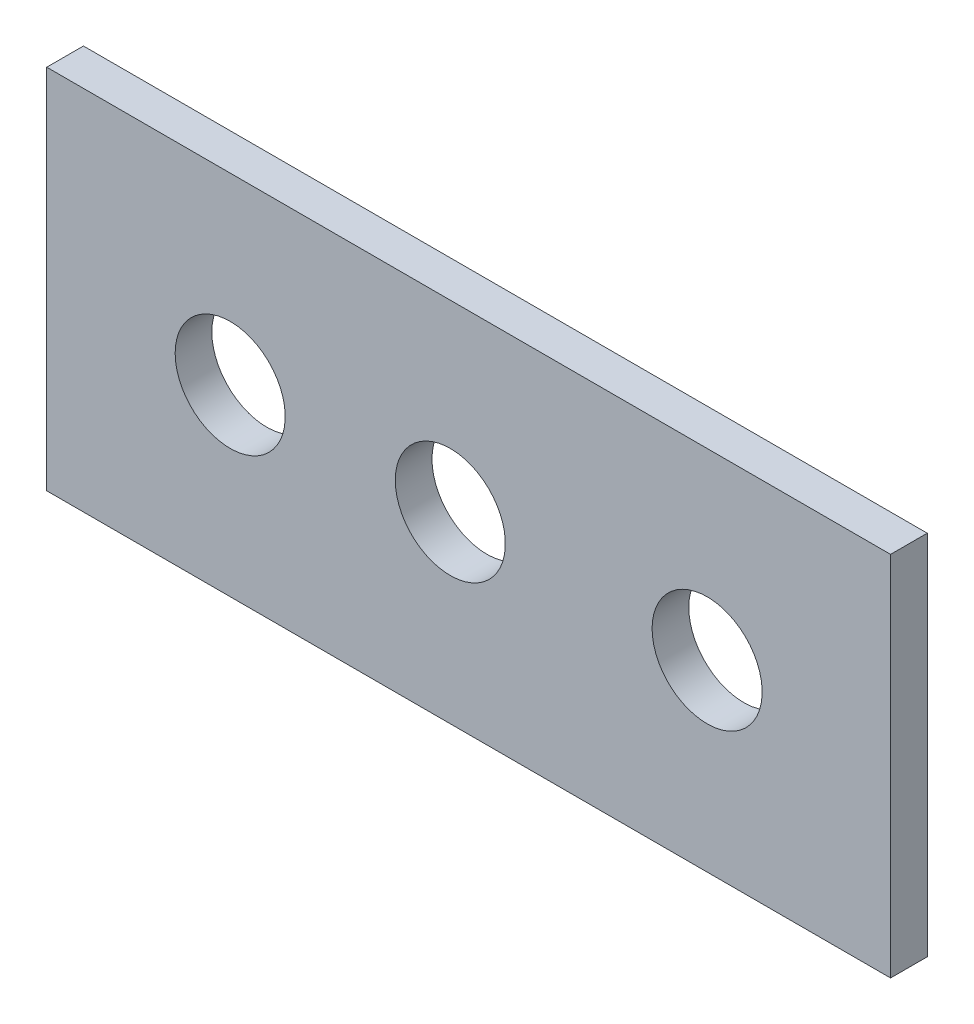
SolidWorks part; units mm, degrees
ref_plane "Front Plane" through (0, 0, 0) normal (0, 0, 1) x (1, 0, 0)
ref_plane "Top Plane" through (0, 0, 0) normal (0, 1, 0) x (1, 0, 0)
ref_plane "Right Plane" through (0, 0, 0) normal (1, 0, 0) x (0, 0, -1)
sketch "Sketch1" plane through (0, 0, 0) normal (0, 1, 0) x (1, 0, 0)
  line L1 (0, 0) -> (-230, 0)
  line L2 (0, 0) -> (0, 10)
  line L3 (0, 10) -> (-230, 10)
  line L4 (-230, 0) -> (-230, 10)
  dimension "D1" = 230
  dimension "D2" = 10
extrude "Boss-Extrude1" add sketch "Sketch1" along normal blind 100
sketch "Sketch2" plane through (0, 0, -10) normal (0, 0, -1) x (-1, 0, 0)
  line L1 (0, 0) -> (230, 0) construction
  line L2 (230, 100) -> (230, 0) construction
  line L3 (0, 100) -> (0, 0) construction
  circle A0 centre (50, 50) radius 15
  circle A1 centre (180, 50) radius 15
  circle A2 centre (120, 50) radius 15
  point P8 (0, 0)
  dimension "D8" = 30
  dimension "D9" = 30
  dimension "D10" = 30
  dimension "D1" = 50
  dimension "D2" = 50
  dimension "D3" = 50
  dimension "D4" = 50
  dimension "D5" = 50
  dimension "D6" = 120
  dimension "D7" = 50
extrude "Cut-Extrude1" cut sketch "Sketch2" against normal blind 10
